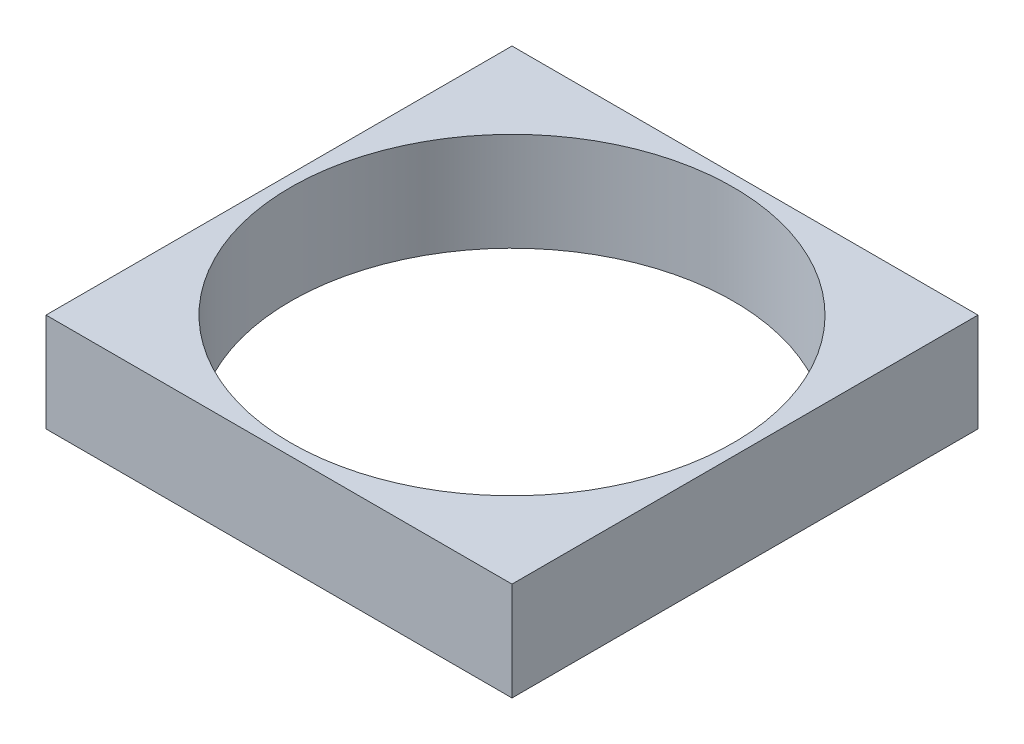
SolidWorks part; units mm, degrees
ref_plane "Front Plane" through (0, 0, 0) normal (0, 0, 1) x (1, 0, 0)
ref_plane "Top Plane" through (0, 0, 0) normal (0, 1, 0) x (1, 0, 0)
ref_plane "Right Plane" through (0, 0, 0) normal (1, 0, 0) x (0, 0, -1)
sketch "Sketch2" plane through (0, 0, 0) normal (0, 1, 0) x (1, 0, 0)
  line L1 (-60, -60) -> (60, -60)
  line L2 (-60, -60) -> (-60, 60)
  line L3 (-60, 60) -> (60, 60)
  line L4 (60, -60) -> (60, 60)
  line L5 (-60, -60) -> (60, 60) construction
  line L6 (-60, 60) -> (60, -60) construction
  circle A0 centre (0, 0) radius 57
  point P0 (0, 0)
  dimension "D3" = 114
  dimension "D1" = 120
  dimension "D2" = 120
extrude "Boss-Extrude1" add sketch "Sketch2" along normal blind 25.4
equation "\"Fan length/width\"= \"D1@Sketch2\""
equation "\"Fan radius\"= \"D3@Sketch2\" / 2"
equation "\"Fan height\"= \"D1@Boss-Extrude1\""
